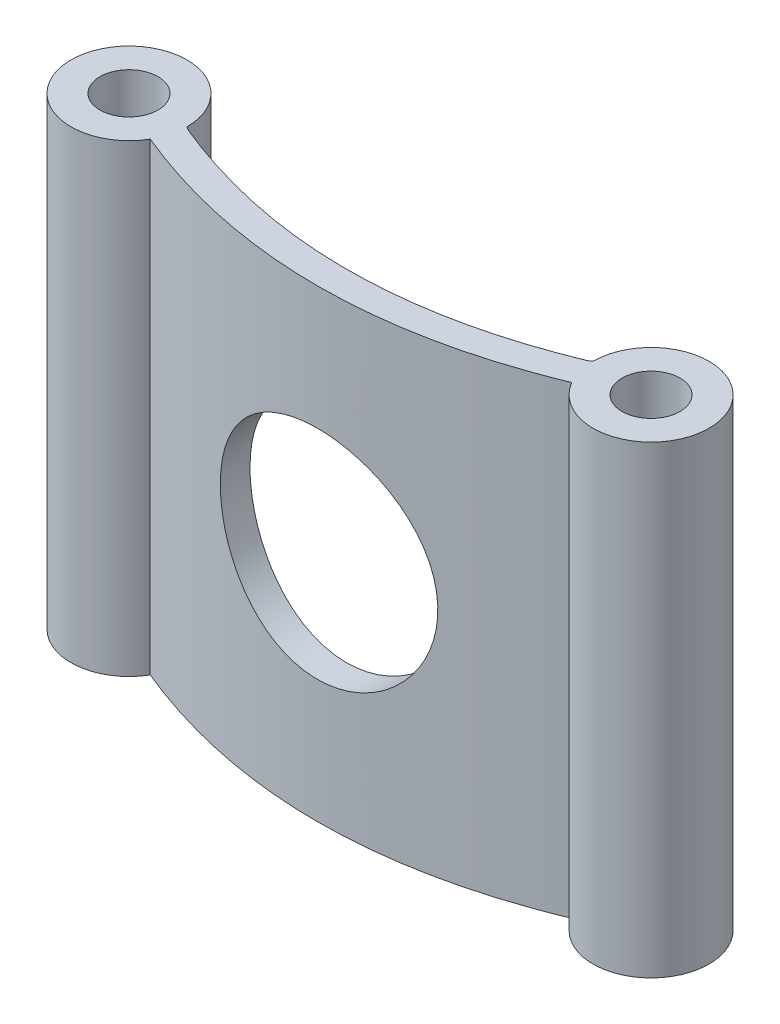
SolidWorks part; units mm, degrees
ref_plane "Front Plane" through (0, 0, 0) normal (0, 0, 1) x (1, 0, 0)
ref_plane "Top Plane" through (0, 0, 0) normal (0, 1, 0) x (1, 0, 0)
ref_plane "Right Plane" through (0, 0, 0) normal (1, 0, 0) x (0, 0, -1)
sketch "Sketch1" plane through (0, 0, 0) normal (0, 1, 0) x (1, 0, 0)
  line L0 (-18, 0) -> (18, 0) construction
  line L1 (0, 0) -> (0, -5) construction
  line L2 (-13.7728, -0.1513) -> (-14, 0)
  line L3 (13.7728, -0.1513) -> (14, 0)
  circle A0 centre (-18, 0) radius 2
  circle A1 centre (18, 0) radius 2
  arc A2 (-14, 0) -> (-14.5359, -2) centre (-18, 0) ccw
  arc A3 (14.5359, -2) -> (14, 0) centre (18, 0) ccw
  spline S0 degree 2 poles (-14.5359, -2) (0, -8) (14.5359, -2) knots 0 0 0 1 1 1
  spline S1 degree 1 poles (-13.7728, -0.1513) (13.7728, -0.1513) knots 0 0 1 1 construction
  spline S2 degree 3 poles (-13.7728, -0.1513) (-13.2002, -0.3877) (-12.0362, -0.8383) (-9.735, -1.6097) (-6.8612, -2.3511) (-3.4277, -2.8821) (0, -3.059) (3.4277, -2.8821) (6.8612, -2.3511) (9.735, -1.6097) (12.0362, -0.8383) (13.2002, -0.3877) (13.7728, -0.1513) knots 0 0 0 0 0.0625 0.125 0.25 0.375 0.5 0.625 0.75 0.875 0.9375 1 1 1 1
  point P3 (0, 0)
  dimension "D2" = 4
  dimension "D3" = 8
  dimension "D1" = 36
  dimension "D4" = 2
  dimension "D5" = 2
  dimension "D6" = 5
  dimension "D7" = 2
extrude "Boss-Extrude1" add sketch "Sketch1" along normal blind 32
sketch "Sketch2" plane through (0, 0, 0) normal (0, 0, 1) x (1, 0, 0)
  line L0 (0, 0) -> (0, 32) construction
  line L1 (-14.5359, 0) -> (14.5359, 0) construction
  line L2 (14.5359, 32) -> (-14.5359, 32) construction
  circle A0 centre (0, 16) radius 7.5
  dimension "D1" = 15
extrude "Cut-Extrude1" cut sketch "Sketch2" along normal blind 25
